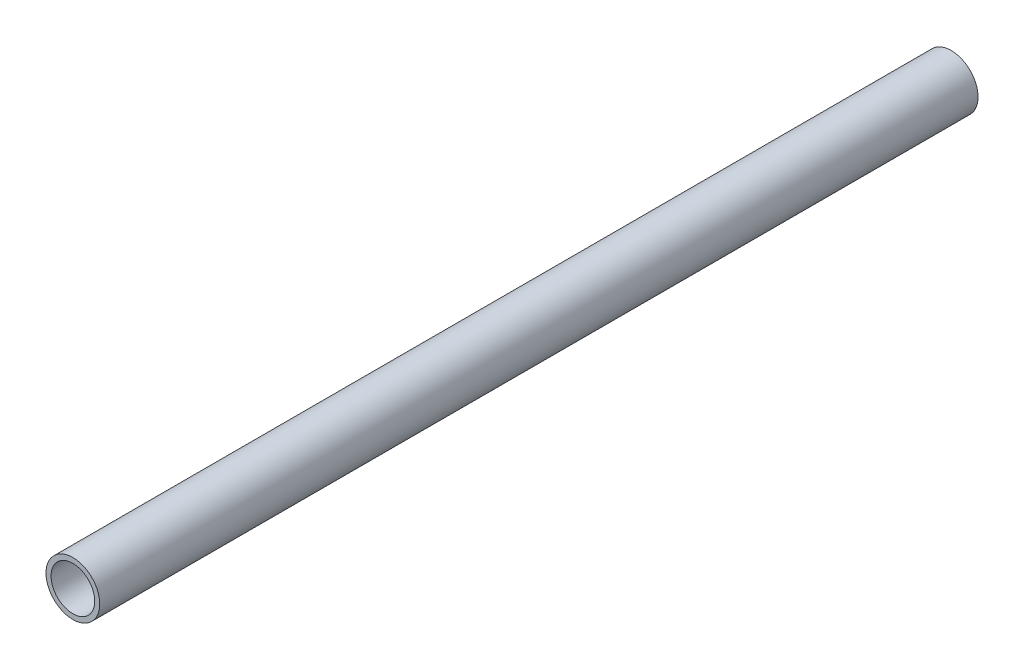
SolidWorks part; units mm, degrees
ref_plane "Alzado" through (0, 0, 0) normal (0, 0, 1) x (1, 0, 0)
ref_plane "Planta" through (0, 0, 0) normal (0, 1, 0) x (1, 0, 0)
ref_plane "Vista lateral" through (0, 0, 0) normal (1, 0, 0) x (0, 0, -1)
sketch "Croquis1" plane through (0, 0, 0) normal (0, 0, 1) x (1, 0, 0)
  circle A0 centre (0, 0) radius 16
  dimension "D1" = 32
extrude "Extruir1" add sketch "Croquis1" along normal mid plane 518
shell "Vaciado1" thickness 3
sketch "Croquis2" plane through (0, 0, -259) normal (0, 0, -1) x (-1, 0, 0)
  circle A0 centre (0, 0) radius 16 construction
  circle A1 centre (0, 0) radius 16
extrude "Extruir2" add sketch "Croquis2" along normal blind 5
